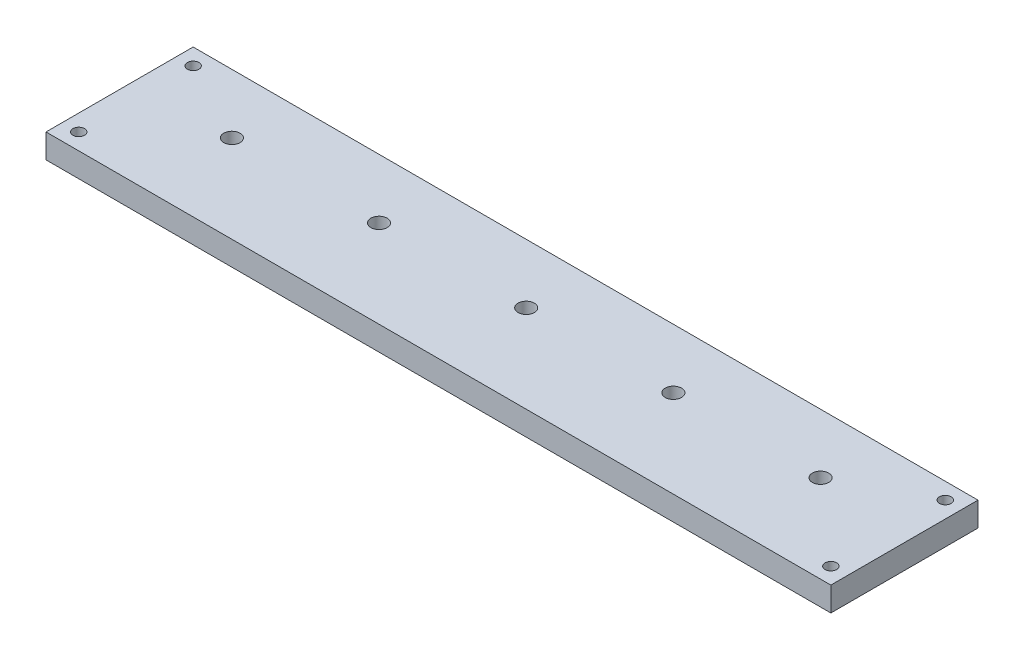
SolidWorks part; units mm, degrees
material "Custom Plastic"
ref_plane "Front Plane" through (0, 0, 0) normal (0, 0, 1) x (1, 0, 0)
ref_plane "Top Plane" through (0, 0, 0) normal (0, 1, 0) x (1, 0, 0)
ref_plane "Right Plane" through (0, 0, 0) normal (1, 0, 0) x (0, 0, -1)
sketch "Sketch1" plane through (0, 0, 0) normal (0, 1, 0) x (1, 0, 0)
  line L0 (0, 28.575) -> (152.4, 28.575)
  line L1 (0, 0) -> (152.4, 0)
  line L2 (0, 0) -> (0, 28.575)
  line L4 (152.4, 0) -> (152.4, 28.575)
  circle A0 centre (19.05, 17.0434) radius 1.5875
  circle A1 centre (47.625, 17.0434) radius 1.5875
  circle A2 centre (76.2, 17.0434) radius 1.5875
  circle A3 centre (104.775, 17.0434) radius 1.5875
  circle A4 centre (133.35, 17.0434) radius 1.5875
  dimension "D8" = 3.175
  dimension "D9" = 3.175
  dimension "D10" = 3.175
  dimension "D11" = 3.175
  dimension "D12" = 3.175
  dimension "D1" = 28.575
  dimension "D2" = 19.05
  dimension "D3" = 19.05
  dimension "D4" = 28.575
  dimension "D5" = 28.575
  dimension "D6" = 28.575
  dimension "D7" = 28.575
  dimension "D16" = 5
extrude "Boss-Extrude1" add sketch "Sketch1" along normal blind 4.699
sketch "Sketch2" plane through (0, 0, 0) normal (0, -1, 0) x (1, 0, 0)
  circle A0 centre (19.05, -17.0434) radius 13.97
  circle A1 centre (47.625, -17.0434) radius 13.97
  circle A2 centre (76.2, -17.0434) radius 13.97
  circle A3 centre (104.775, -17.0434) radius 13.97
  circle A4 centre (133.35, -17.0434) radius 13.97
  dimension "D1" = 27.94
extrude "Cut-Extrude1" cut sketch "Sketch2" against normal blind 1.778
hole_wizard "#4-40 Tapped Hole1" positions "Sketch5" profile "Sketch7" tap size "#4-40" standard "ANSI Inch" end condition up to next
sketch "Sketch5" plane through (0, 4.699, 0) normal (0, 1, 0) x (1, 0, 0)
  line L0 (0, 0) -> (0, 28.575) construction
  line L2 (0, 0) -> (152.4, 0) construction
  line L4 (152.4, 0) -> (152.4, 28.575) construction
  line L5 (0, 28.575) -> (11.1644, 28.575) construction
  line L6 (141.2356, 28.575) -> (152.4, 28.575) construction
  point P0 (3.175, 25.4)
  point P2 (3.175, 3.175)
  point P4 (149.225, 3.175)
  point P6 (149.225, 25.4)
  dimension "D1" = 3.175
  dimension "D2" = 3.175
  dimension "D3" = 3.175
  dimension "D4" = 3.175
  dimension "D5" = 3.175
  dimension "D6" = 3.175
  dimension "D7" = 3.175
  dimension "D8" = 3.175
sketch "Sketch7" plane through (3.175, 4.699, -25.4) normal (1, 0, 0) x (0, 0, 1)
  line L0 (0, 0) -> (0, 4.699)
  line L1 (0, 4.699) -> (1.1303, 4.699)
  line L2 (1.1303, 4.699) -> (1.1303, 0)
  line L5 (1.1303, 0) -> (0, 0)
  line L11 (0, -6.35) -> (0, 107.95) construction
  dimension "Thru Tap Drill Dia." = 2.2606
  dimension "Thru Tap Drill Depth" = 4.699
cosmetic thread "Hole Thread1" parameters "D2"=2.8448
cosmetic thread "Hole Thread2" parameters "D2"=2.8448
cosmetic thread "Hole Thread3" parameters "D2"=2.8448
cosmetic thread "Hole Thread4" parameters "D2"=2.8448
